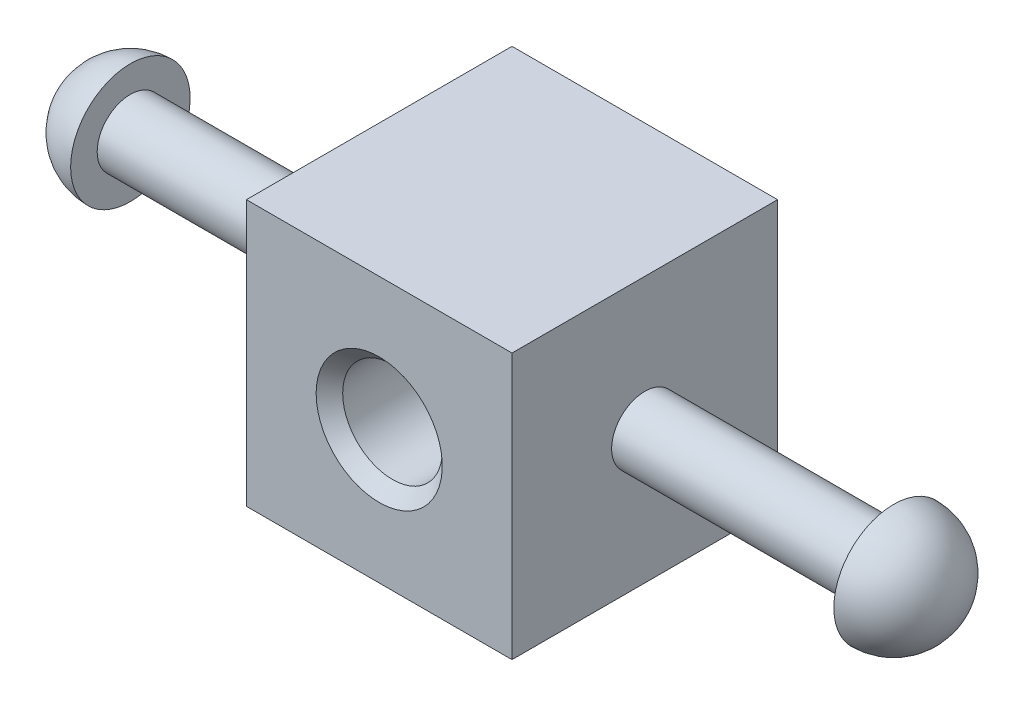
SolidWorks part; units mm, degrees
ref_plane "Front Plane" through (0, 0, 0) normal (0, 0, 1) x (1, 0, 0)
ref_plane "Top Plane" through (0, 0, 0) normal (0, 1, 0) x (1, 0, 0)
ref_plane "Right Plane" through (0, 0, 0) normal (1, 0, 0) x (0, 0, -1)
sketch "Sketch1" plane through (0, 0, 0) normal (0, 1, 0) x (1, 0, 0)
  line L1 (-12.7, -12.7) -> (12.7, -12.7)
  line L2 (-12.7, -12.7) -> (-12.7, 12.7)
  line L3 (-12.7, 12.7) -> (12.7, 12.7)
  line L4 (12.7, -12.7) -> (12.7, 12.7)
  line L5 (-12.7, -12.7) -> (12.7, 12.7) construction
  line L6 (-12.7, 12.7) -> (12.7, -12.7) construction
  point P0 (0, 0)
  dimension "D1" = 25.4
  dimension "D2" = 25.4
extrude "Boss-Extrude1" add sketch "Sketch1" along normal blind 25.4
sketch "Sketch2" plane through (0, 0, 12.7) normal (0, 0, 1) x (1, 0, 0)
  line L1 (-12.7, 25.4) -> (12.7, 25.4) construction
  line L2 (12.7, 25.4) -> (12.7, 0) construction
  circle A0 centre (0, 12.7) radius 4.7625
  point P2 (0, 0)
  dimension "D1" = 9.525
  dimension "D2" = 12.7
  dimension "D3" = 12.7
extrude "Cut-Extrude1" cut sketch "Sketch2" against normal blind 25.4
chamfer "Chamfer1" distance 1.27 angle 45 1 edges at (4.7625, 12.7, 12.7)
chamfer "Chamfer2" distance 1.27 angle 45 1 edges at (4.7625, 12.7, -12.7)
sketch "Sketch3" plane through (12.7, 0, 0) normal (1, 0, 0) x (0, 0, -1)
  line L0 (0, 0) -> (0, 25.4)
  line L1 (-12.7, 0) -> (12.7, 0) construction
  line L2 (-12.7, 25.4) -> (12.7, 25.4) construction
ref_plane "Plane1" through (0, 0, 0) normal (0, 0, 1) x (1, 0, 0)
sketch "Sketch5" plane through (0, 0, 0) normal (0, 0, 1) x (1, 0, 0)
  line L0 (0, 0) -> (0, 12.7)
  line L1 (12.7, 15.875) -> (36.4971, 15.875)
  line L2 (12.7, 0) -> (12.7, 25.4) construction
  line L3 (36.4971, 15.875) -> (36.4971, 18.415)
  line L5 (12.7, 12.7) -> (26.4739, 12.7)
  arc A0 (42.2121, 12.7) -> (36.4971, 18.415) centre (36.4971, 12.7) ccw
  dimension "D1" = 11.43
  dimension "D2" = 3.175
revolve "Revolve-Thin4" add sketch "Sketch5" angle 360 about L5
sketch "Sketch6" plane through (0, 0, 12.7) normal (0, 0, 1) x (1, 0, 0)
  line L0 (0, 0) -> (0, 25.4)
  line L1 (-12.7, 0) -> (12.7, 0) construction
  line L2 (-12.7, 25.4) -> (12.7, 25.4) construction
ref_plane "Plane2" through (0, 0, 0) normal (-1, 0, 0) x (0, 0, 1)
mirror "Mirror1" about plane through (0, 0, 0) normal (-1, 0, 0) of "Revolve-Thin4"
